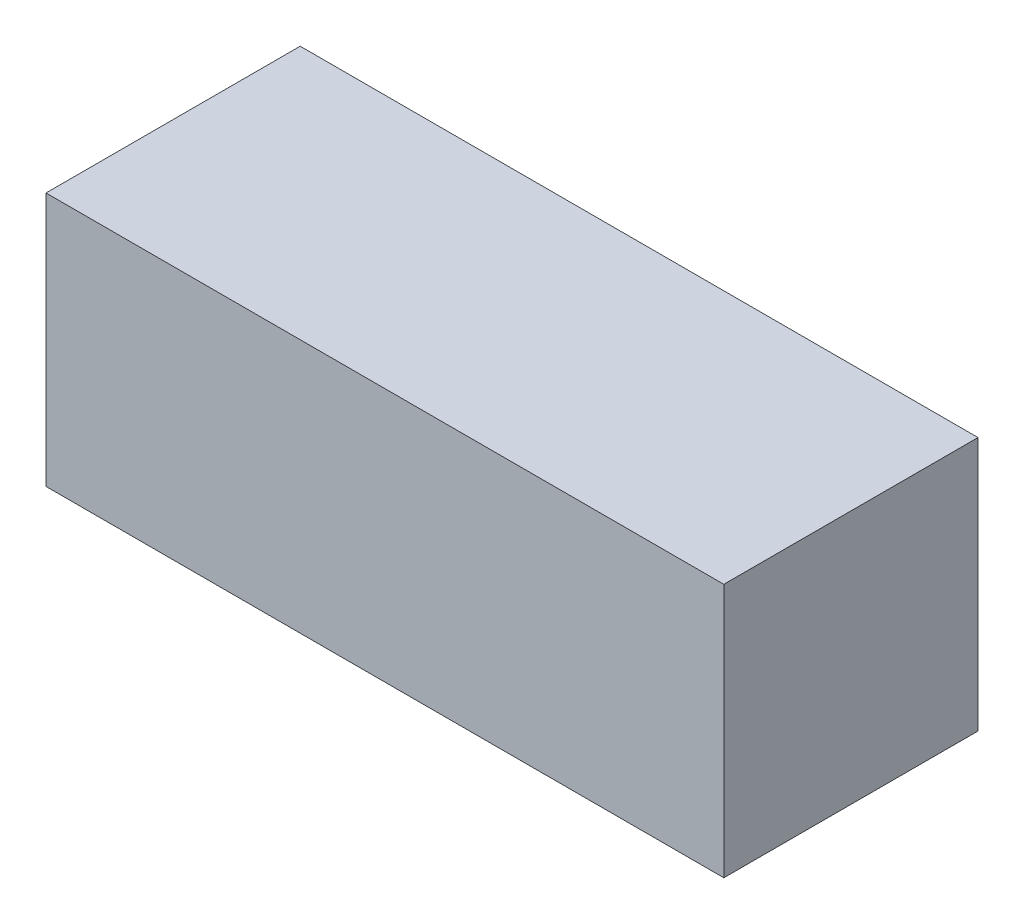
SolidWorks part; units mm, degrees
ref_plane "Plan de face" through (0, 0, 0) normal (0, 0, 1) x (1, 0, 0)
ref_plane "Plan de dessus" through (0, 0, 0) normal (0, 1, 0) x (1, 0, 0)
ref_plane "Plan de droite" through (0, 0, 0) normal (1, 0, 0) x (0, 0, -1)
sketch "Esquisse1" plane through (0, 0, 0) normal (0, 0, 1) x (1, 0, 0)
  line L1 (0, 0) -> (16, 0)
  line L2 (0, 0) -> (0, 6)
  line L3 (0, 6) -> (16, 6)
  line L4 (16, 0) -> (16, 6)
  dimension "D1" = 6
  dimension "D2" = 16
extrude "Extrusion1" add sketch "Esquisse1" along normal blind 6
